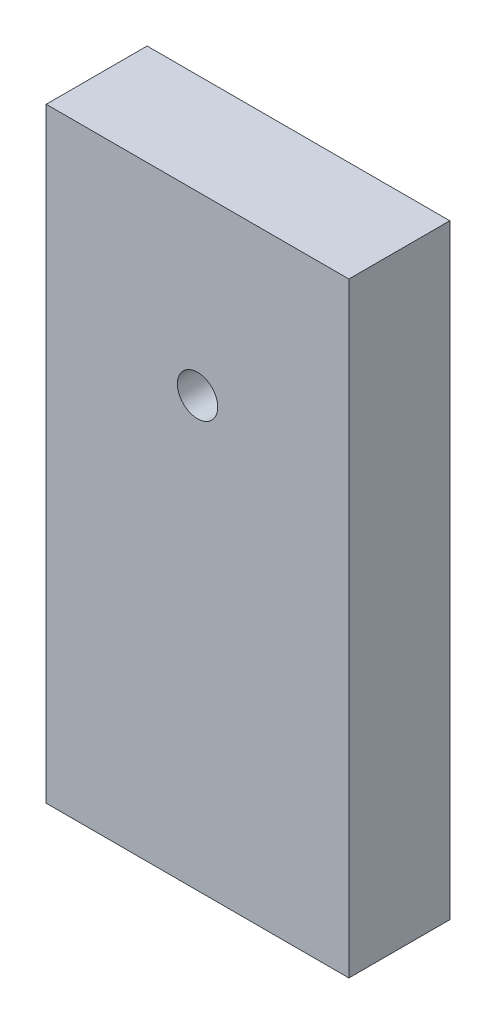
SolidWorks part; units mm, degrees
ref_plane "Plan de face" through (0, 0, 0) normal (0, 0, 1) x (1, 0, 0)
ref_plane "Plan de dessus" through (0, 0, 0) normal (0, 1, 0) x (1, 0, 0)
ref_plane "Plan de droite" through (0, 0, 0) normal (1, 0, 0) x (0, 0, -1)
sketch "Esquisse1" plane through (0, 0, 0) normal (0, 0, 1) x (1, 0, 0)
  line L1 (-15, 30) -> (15, 30)
  line L2 (-15, 30) -> (-15, -30)
  line L3 (-15, -30) -> (15, -30)
  line L4 (15, 30) -> (15, -30)
  line L5 (-15, 30) -> (15, -30) construction
  line L6 (-15, -30) -> (15, 30) construction
  point P0 (0, 0)
  dimension "D1" = 60
  dimension "D2" = 30
extrude "Boss.-Extru.1" add sketch "Esquisse1" along normal blind 10
sketch "Esquisse2" plane through (0, 0, 10) normal (0, 0, 1) x (1, 0, 0)
  line L0 (-15, -30) -> (15, -30) construction
  line L1 (-15, 30) -> (-15, -30) construction
  circle A0 centre (0, 12.5) radius 2
  dimension "D2" = 4
  dimension "D1" = 42.5
  dimension "D3" = 15
extrude "Enlèv. mat.-Extru.1" cut sketch "Esquisse2" against normal through all
sketch "Esquisse3" plane through (0, -30, 0) normal (0, -1, 0) x (1, 0, 0)
  line L1 (-15, 10) -> (15, 10)
  line L2 (-15, 10) -> (-15, 0)
  line L3 (-15, 0) -> (15, 0)
  line L4 (15, 10) -> (15, 0)
